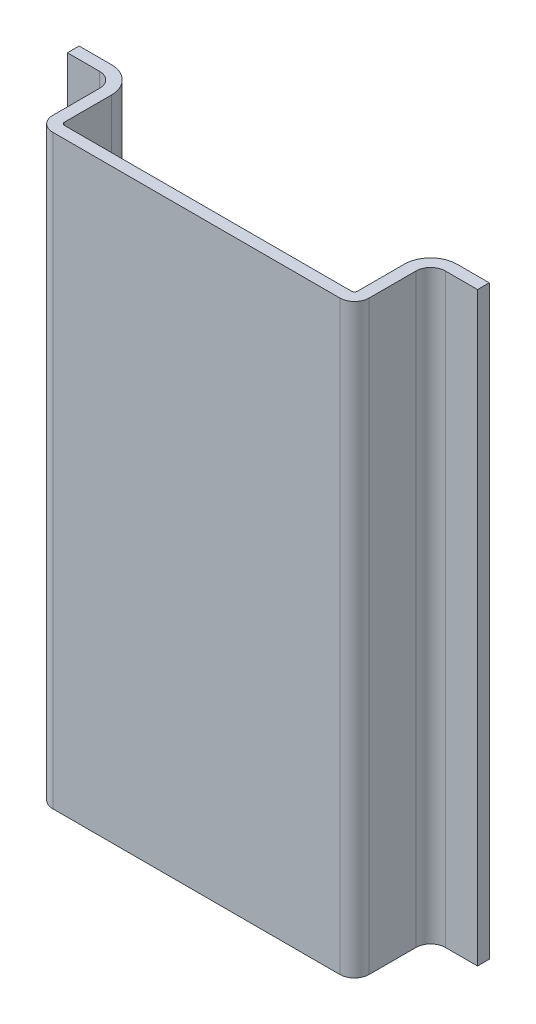
SolidWorks part; units mm, degrees
ref_plane "Front Plane" through (0, 0, 0) normal (0, 0, 1) x (1, 0, 0)
ref_plane "Top Plane" through (0, 0, 0) normal (0, 1, 0) x (1, 0, 0)
ref_plane "Right Plane" through (0, 0, 0) normal (1, 0, 0) x (0, 0, -1)
sketch3d "3DSketch1"
  line L0 (0, 0, 0) -> (0, 50, 0)
  dimension "D1" = 50
other "Omega TS-35(1)"
ref_plane "Plane1" through (0, 0, 0) normal (0, 1, 0) x (1, 0, 0)
sketch "Sketch2" plane through (0, 0, 0) normal (0, 1, 0) x (1, 0, 0)
  line L0 (12.25, 0) -> (-12.25, 0)
  line L1 (13.5, 1.25) -> (13.5, 5.25)
  line L2 (14.75, 6.5) -> (17.5, 6.5)
  line L3 (-14.75, 6.5) -> (-17.5, 6.5)
  line L4 (-13.5, 1.25) -> (-13.5, 5.25)
  line L5 (14.75, 7.5) -> (17.5, 7.5)
  line L6 (12.5, 1.25) -> (12.5, 5.25)
  line L7 (12.25, 1) -> (-12.25, 1)
  line L8 (-12.5, 1.25) -> (-12.5, 5.25)
  line L9 (-14.75, 7.5) -> (-17.5, 7.5)
  line L10 (17.5, 6.5) -> (17.5, 7.5)
  line L11 (-17.5, 6.5) -> (-17.5, 7.5)
  arc A0 (13.5, 5.25) -> (14.75, 6.5) centre (14.75, 5.25) cw
  arc A1 (-14.75, 6.5) -> (-13.5, 5.25) centre (-14.75, 5.25) cw
  arc A2 (-12.25, 0) -> (-13.5, 1.25) centre (-12.25, 1.25) cw
  arc A3 (12.25, 0) -> (13.5, 1.25) centre (12.25, 1.25) ccw
  arc A4 (12.5, 5.25) -> (14.75, 7.5) centre (14.75, 5.25) cw
  arc A5 (12.25, 1) -> (12.5, 1.25) centre (12.25, 1.25) ccw
  arc A6 (-12.25, 1) -> (-12.5, 1.25) centre (-12.25, 1.25) cw
  arc A7 (-14.75, 7.5) -> (-12.5, 5.25) centre (-14.75, 5.25) cw
  point P2 (0, 0)
  point P29 (0, 0)
  point P30 (0, 0)
